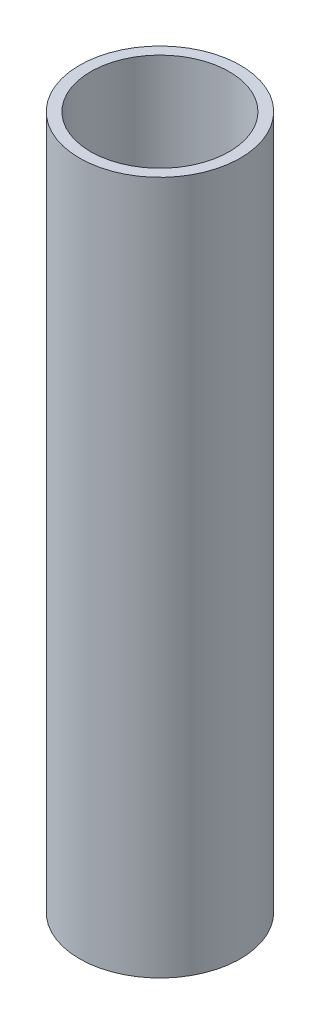
SolidWorks part; units mm, degrees
material "Thornel Mat VMA"
ref_plane "Front Plane" through (0, 0, 0) normal (0, 0, 1) x (1, 0, 0)
ref_plane "Top Plane" through (0, 0, 0) normal (0, 1, 0) x (1, 0, 0)
ref_plane "Right Plane" through (0, 0, 0) normal (1, 0, 0) x (0, 0, -1)
sketch "Sketch2" plane through (0, 0, 0) normal (0, 1, 0) x (1, 0, 0)
  circle A0 centre (0, 0) radius 7.366
  circle A1 centre (0, 0) radius 6.35
  dimension "D1" = 12.7
  dimension "D2" = 1.016
extrude "Boss-Extrude1" add sketch "Sketch2" along normal blind 63.5
